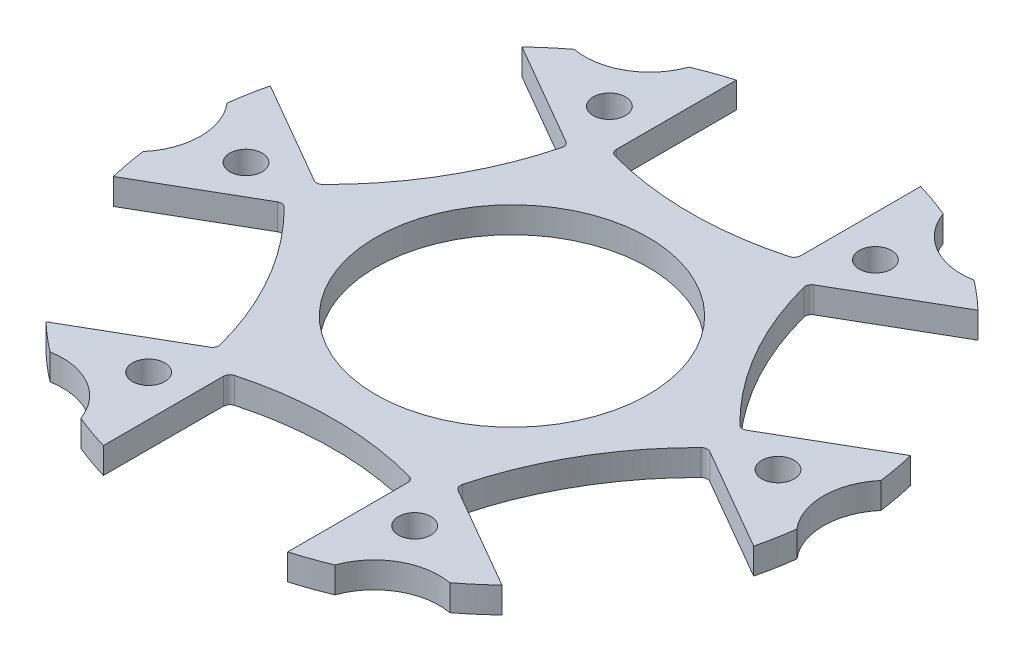
SolidWorks part; units mm, degrees
material "Hexcel AS4C (3000 丝)"
ref_plane "前视基准面" through (0, 0, 0) normal (0, 0, 1) x (1, 0, 0)
ref_plane "上视基准面" through (0, 0, 0) normal (0, 1, 0) x (1, 0, 0)
ref_plane "右视基准面" through (0, 0, 0) normal (1, 0, 0) x (0, 0, -1)
sketch "草图1" plane through (0, 0, 0) normal (0, 1, 0) x (1, 0, 0)
  circle A0 centre (0, 0) radius 25.4
  circle A1 centre (0, 0) radius 10.5
  dimension "D1" = 50.8
  dimension "D2" = 21
extrude "凸台-拉伸1" add sketch "草图1" along normal blind 2
sketch "草图2" plane through (0, 2, 0) normal (0, 1, 0) x (1, 0, 0)
  line L0 (0, 25.4) -> (0, -24.9458) construction
  line L1 (-7.1, 24.3875) -> (-7.1, 14.7625)
  line L2 (7.1, 24.3875) -> (7.1, 14.7625)
  line L3 (17.5702, 18.3425) -> (9.2347, 13.53)
  line L4 (7.1, 25.4) -> (7.1, -24.9458) construction
  line L5 (-7.1, 25.4) -> (-7.1, -24.9458) construction
  line L6 (24.6702, 6.045) -> (16.3347, 1.2325)
  line L7 (24.6702, -6.045) -> (16.3347, -1.2325)
  line L8 (17.5702, -18.3425) -> (9.2347, -13.53)
  line L9 (7.1, -24.3875) -> (7.1, -14.7625)
  line L10 (-7.1, -24.3875) -> (-7.1, -14.7625)
  line L11 (-17.5702, -18.3425) -> (-9.2347, -13.53)
  line L12 (-24.6702, -6.045) -> (-16.3347, -1.2325)
  line L13 (-24.6702, 6.045) -> (-16.3347, 1.2325)
  line L14 (-17.5702, 18.3425) -> (-9.2347, 13.53)
  circle A0 centre (0, 0) radius 25.4 construction
  arc A1 (7.1, 24.3875) -> (-7.1, 24.3875) centre (0, 0) ccw
  arc A2 (-7.1, 14.7625) -> (7.1, 14.7625) centre (0, 39.15) ccw
  arc A3 (24.6702, 6.045) -> (17.5702, 18.3425) centre (0, 0) ccw
  arc A4 (9.2347, 13.53) -> (16.3347, 1.2325) centre (33.9049, 19.575) ccw
  arc A5 (17.5702, -18.3425) -> (24.6702, -6.045) centre (0, 0) ccw
  arc A6 (16.3347, -1.2325) -> (9.2347, -13.53) centre (33.9049, -19.575) ccw
  arc A7 (-7.1, -24.3875) -> (7.1, -24.3875) centre (0, 0) ccw
  arc A8 (7.1, -14.7625) -> (-7.1, -14.7625) centre (0, -39.15) ccw
  arc A9 (-24.6702, -6.045) -> (-17.5702, -18.3425) centre (0, 0) ccw
  arc A10 (-9.2347, -13.53) -> (-16.3347, -1.2325) centre (-33.9049, -19.575) ccw
  arc A11 (-17.5702, 18.3425) -> (-24.6702, 6.045) centre (0, 0) ccw
  arc A12 (-16.3347, 1.2325) -> (-9.2347, 13.53) centre (-33.9049, 19.575) ccw
  point P43 (0, 0)
  dimension "D3" = 50.8
  dimension "D4" = 39.15
  dimension "D1" = 7.1
  dimension "D2" = 7.1
  dimension "D5" = 6
extrude "切除-拉伸1" cut sketch "草图2" against normal through all
sketch "草图3" plane through (0, 2, 0) normal (0, 1, 0) x (1, 0, 0)
  line L0 (-12.7, 21.997) -> (12.7, -21.997) construction
  circle A0 centre (0, 0) radius 20.5 construction
  arc A1 (-7.1, 24.3875) -> (-17.5702, 18.3425) centre (0, 0) ccw construction
  arc A2 (7.1, -24.3875) -> (17.5702, -18.3425) centre (0, 0) ccw construction
  circle A3 centre (-10.25, 17.7535) radius 1.25
  circle A4 centre (10.25, 17.7535) radius 1.25
  circle A5 centre (20.5, 0) radius 1.25
  circle A6 centre (10.25, -17.7535) radius 1.25
  circle A7 centre (-10.25, -17.7535) radius 1.25
  circle A8 centre (-20.5, 0) radius 1.25
  circle A9 centre (-29, 0) radius 5
  circle A10 centre (-14.5, 25.1147) radius 5
  circle A11 centre (14.5, 25.1147) radius 5
  circle A12 centre (29, 0) radius 5
  circle A13 centre (14.5, -25.1147) radius 5
  circle A14 centre (-14.5, -25.1147) radius 5
  point P25 (0, 0)
  point P38 (0, 0)
  dimension "D1" = 41
  dimension "D2" = 2.5
  dimension "D4" = 10
  dimension "D5" = 29
  dimension "D3" = 6
  dimension "D6" = 6
extrude "切除-拉伸2" cut sketch "草图3" against normal through all
fillet "圆角1" radius 0.5 12 edges at (-7.1, 1, -14.7625) (7.1, 1, -14.7625) (9.2347, 1, -13.53) (16.3347, 1, -1.2325) (16.3347, 1, 1.2325) (9.2347, 1, 13.53) (7.1, 1, 14.7625) (-7.1, 1, 14.7625) (-9.2347, 1, 13.53) (-16.3347, 1, -1.2325) (-9.2347, 1, -13.53) (-16.3347, 1, 1.2325)
